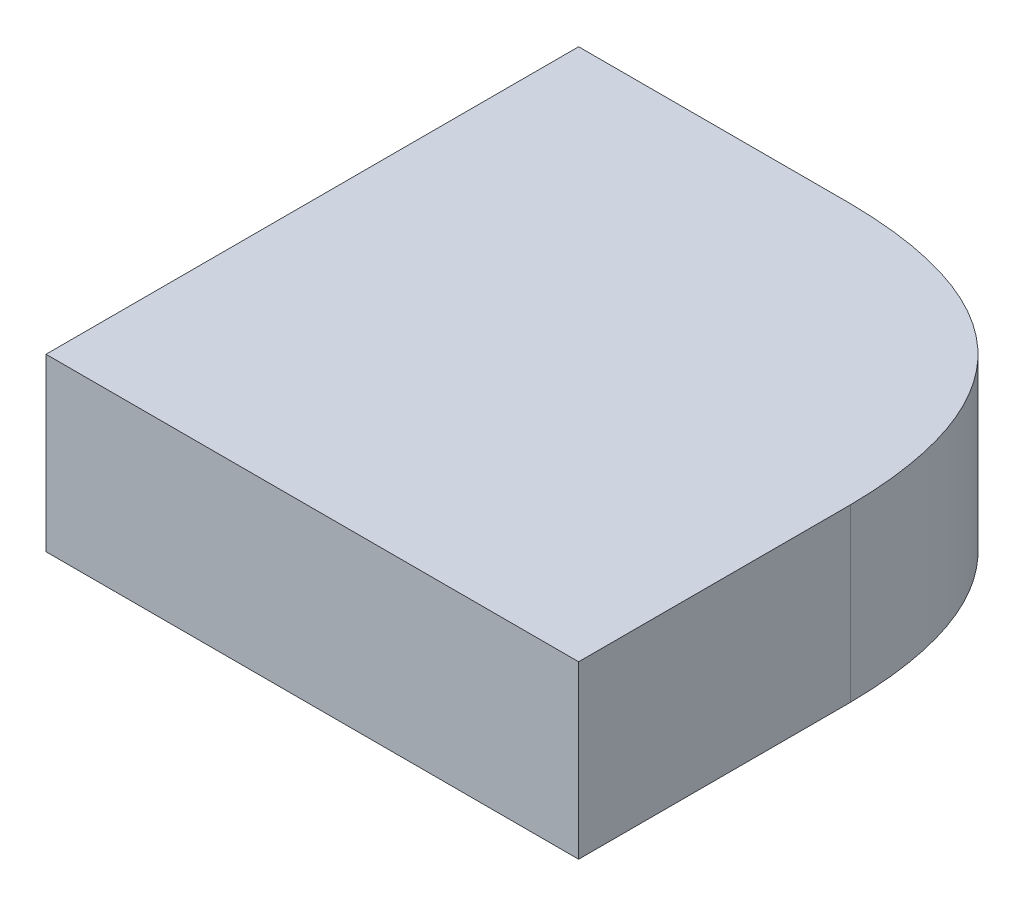
SolidWorks part; units mm, degrees
ref_plane "Front Plane" through (0, 0, 0) normal (0, 0, 1) x (1, 0, 0)
ref_plane "Top Plane" through (0, 0, 0) normal (0, 1, 0) x (1, 0, 0)
ref_plane "Right Plane" through (0, 0, 0) normal (1, 0, 0) x (0, 0, -1)
sketch "Sketch1" plane through (0, 0, 0) normal (0, 1, 0) x (1, 0, 0)
  line L3 (0, 12.4558) -> (-12.4558, 12.4558)
  line L4 (12.4558, 0) -> (12.4558, -12.4558)
  line L5 (12.4558, -12.4558) -> (-12.4558, -12.4558)
  line L6 (-12.4558, -12.4558) -> (-12.4558, 12.4558)
  line L10 (0, 12.4558) -> (0.254, 12.4558)
  line L11 (12.4558, 0) -> (12.4558, 0.254)
  spline S0 degree 2 poles (0.254, 12.4558) (12.324, 12.324) (12.4558, 0.254) knots 0 0 0 1 1 1
extrude "Boss-Extrude1" add sketch "Sketch1" along normal blind 8
